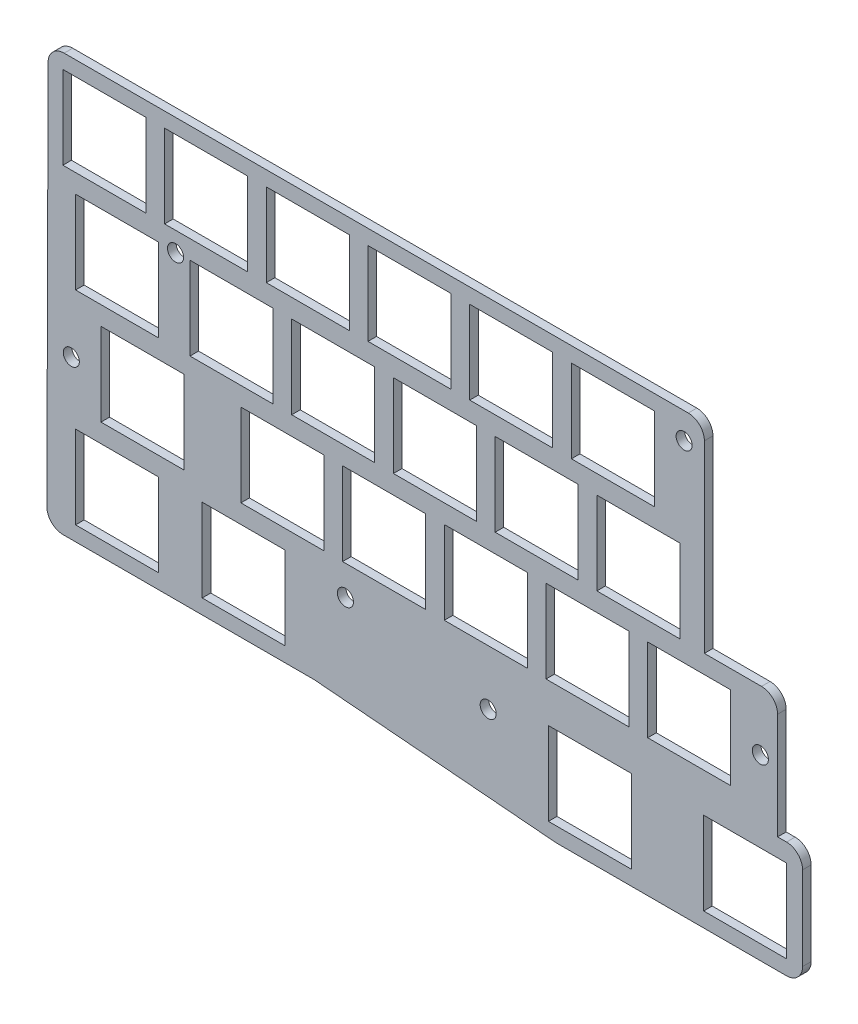
SolidWorks part; units mm, degrees
ref_plane "Front Plane" through (0, 0, 0) normal (0, 0, 1) x (1, 0, 0)
ref_plane "Top Plane" through (0, 0, 0) normal (0, 1, 0) x (1, 0, 0)
ref_plane "Right Plane" through (0, 0, 0) normal (1, 0, 0) x (0, 0, -1)
sketch "Sketch1" plane through (0, 0, 0) normal (0, 0, 1) x (1, 0, 0)
  line B0 (80.807, -9.202) -> (80.807, 37.7092)
  line B1 (77.8051, 40.7092) -> (-72.1545, 40.6131)
  arc B2 (-72.1545, 40.6131) -> (-75.1525, 37.6227) centre (-72.1526, 37.6131) ccw
  line B3 (-75.1525, 37.6227) -> (-75.3833, -34.3792)
  arc B4 (-75.3833, -34.3792) -> (-72.3833, -37.3888) centre (-72.3833, -34.3888) ccw
  line B5 (-72.3833, -37.3888) -> (-25.6137, -37.3888)
  arc B6 (-25.3626, -37.3994) -> (-25.6137, -37.3888) centre (-25.6137, -40.3888) ccw
  line B7 (-25.3626, -37.3994) -> (19.6317, -41.1783)
  arc B8 (19.6317, -41.1783) -> (19.8828, -41.1888) centre (19.8828, -38.1888) ccw
  line B9 (19.8828, -41.1888) -> (68.1448, -41.1888)
  arc B10 (68.1448, -41.1888) -> (70.9908, -39.1375) centre (68.1448, -38.1888) ccw
  line B11 (70.9908, -39.1375) -> (80.6531, -10.1507)
  arc B12 (80.6531, -10.1507) -> (80.807, -9.202) centre (77.807, -9.202) ccw
  arc B13 (80.807, 37.7092) -> (77.8051, 40.7092) centre (77.807, 37.7092) ccw
  circle B14 centre (-19.613, -21.1888) radius 1.5
  circle B15 centre (7.057, -25.9388) radius 1.5
  circle B16 centre (43.657, 35.8112) radius 1.5
  circle B17 centre (-70.818, -7.8888) radius 1.5
  circle B18 centre (57.907, -7.8888) radius 1.5
  circle B19 centre (-51.343, 18.7112) radius 1.5
  line B20 (-72.393, 22.3612) -> (-56.893, 22.3612)
  line B21 (-56.893, 22.3612) -> (-56.893, 37.8612)
  line B22 (-56.893, 37.8612) -> (-72.393, 37.8612)
  line B23 (-72.393, 37.8612) -> (-72.393, 22.3612)
  line B24 (-53.393, 22.3612) -> (-37.893, 22.3612)
  line B25 (-37.893, 22.3612) -> (-37.893, 37.8612)
  line B26 (-37.893, 37.8612) -> (-53.393, 37.8612)
  line B27 (-53.393, 37.8612) -> (-53.393, 22.3612)
  line B28 (-34.393, 22.3612) -> (-18.893, 22.3612)
  line B29 (-18.893, 22.3612) -> (-18.893, 37.8612)
  line B30 (-18.893, 37.8612) -> (-34.393, 37.8612)
  line B31 (-34.393, 37.8612) -> (-34.393, 22.3612)
  line B32 (-15.393, 22.3612) -> (0.107, 22.3612)
  line B33 (0.107, 22.3612) -> (0.107, 37.8612)
  line B34 (0.107, 37.8612) -> (-15.393, 37.8612)
  line B35 (-15.393, 37.8612) -> (-15.393, 22.3612)
  line B36 (3.607, 22.3612) -> (19.107, 22.3612)
  line B37 (19.107, 22.3612) -> (19.107, 37.8612)
  line B38 (19.107, 37.8612) -> (3.607, 37.8612)
  line B39 (3.607, 37.8612) -> (3.607, 22.3612)
  line B40 (22.607, 22.3612) -> (38.107, 22.3612)
  line B41 (38.107, 22.3612) -> (38.107, 37.8612)
  line B42 (38.107, 37.8612) -> (22.607, 37.8612)
  line B43 (22.607, 37.8612) -> (22.607, 22.3612)
  line B44 (-70.018, 3.3612) -> (-54.518, 3.3612)
  line B45 (-54.518, 3.3612) -> (-54.518, 18.8612)
  line B46 (-54.518, 18.8612) -> (-70.018, 18.8612)
  line B47 (-70.018, 18.8612) -> (-70.018, 3.3612)
  line B48 (-48.643, 3.3612) -> (-33.143, 3.3612)
  line B49 (-33.143, 3.3612) -> (-33.143, 18.8612)
  line B50 (-33.143, 18.8612) -> (-48.643, 18.8612)
  line B51 (-48.643, 18.8612) -> (-48.643, 3.3612)
  line B52 (-29.643, 3.3612) -> (-14.143, 3.3612)
  line B53 (-14.143, 3.3612) -> (-14.143, 18.8612)
  line B54 (-14.143, 18.8612) -> (-29.643, 18.8612)
  line B55 (-29.643, 18.8612) -> (-29.643, 3.3612)
  line B56 (-10.643, 3.3612) -> (4.857, 3.3612)
  line B57 (4.857, 3.3612) -> (4.857, 18.8612)
  line B58 (4.857, 18.8612) -> (-10.643, 18.8612)
  line B59 (-10.643, 18.8612) -> (-10.643, 3.3612)
  line B60 (8.357, 3.3612) -> (23.857, 3.3612)
  line B61 (23.857, 3.3612) -> (23.857, 18.8612)
  line B62 (23.857, 18.8612) -> (8.357, 18.8612)
  line B63 (8.357, 18.8612) -> (8.357, 3.3612)
  line B64 (27.357, 3.3612) -> (42.857, 3.3612)
  line B65 (42.857, 3.3612) -> (42.857, 18.8612)
  line B66 (42.857, 18.8612) -> (27.357, 18.8612)
  line B67 (27.357, 18.8612) -> (27.357, 3.3612)
  line B68 (-65.268, -15.6388) -> (-49.768, -15.6388)
  line B69 (-49.768, -15.6388) -> (-49.768, -0.1388)
  line B70 (-49.768, -0.1388) -> (-65.268, -0.1388)
  line B71 (-65.268, -0.1388) -> (-65.268, -15.6388)
  line B72 (-39.143, -15.6388) -> (-23.643, -15.6388)
  line B73 (-23.643, -15.6388) -> (-23.643, -0.1388)
  line B74 (-23.643, -0.1388) -> (-39.143, -0.1388)
  line B75 (-39.143, -0.1388) -> (-39.143, -15.6388)
  line B76 (-20.143, -15.6388) -> (-4.643, -15.6388)
  line B77 (-4.643, -15.6388) -> (-4.643, -0.1388)
  line B78 (-4.643, -0.1388) -> (-20.143, -0.1388)
  line B79 (-20.143, -0.1388) -> (-20.143, -15.6388)
  line B80 (-1.143, -15.6388) -> (14.357, -15.6388)
  line B81 (14.357, -15.6388) -> (14.357, -0.1388)
  line B82 (14.357, -0.1388) -> (-1.143, -0.1388)
  line B83 (-1.143, -0.1388) -> (-1.143, -15.6388)
  line B84 (17.857, -15.6388) -> (33.357, -15.6388)
  line B85 (33.357, -15.6388) -> (33.357, -0.1388)
  line B86 (33.357, -0.1388) -> (17.857, -0.1388)
  line B87 (17.857, -0.1388) -> (17.857, -15.6388)
  line B88 (36.857, -15.6388) -> (52.357, -15.6388)
  line B89 (52.357, -15.6388) -> (52.357, -0.1388)
  line B90 (52.357, -0.1388) -> (36.857, -0.1388)
  line B91 (36.857, -0.1388) -> (36.857, -15.6388)
  line B92 (-70.018, -34.6388) -> (-54.518, -34.6388)
  line B93 (-54.518, -34.6388) -> (-54.518, -19.1388)
  line B94 (-54.518, -19.1388) -> (-70.018, -19.1388)
  line B95 (-70.018, -19.1388) -> (-70.018, -34.6388)
  line B96 (-46.363, -34.6388) -> (-30.863, -34.6388)
  line B97 (-30.863, -34.6388) -> (-30.863, -19.1388)
  line B98 (-30.863, -19.1388) -> (-46.363, -19.1388)
  line B99 (-46.363, -19.1388) -> (-46.363, -34.6388)
  line B100 (18.307, -38.4388) -> (33.807, -38.4388)
  line B101 (33.807, -38.4388) -> (33.807, -22.9388)
  line B102 (33.807, -22.9388) -> (18.307, -22.9388)
  line B103 (18.307, -22.9388) -> (18.307, -38.4388)
  line B104 (47.307, -38.4388) -> (62.807, -38.4388)
  line B105 (62.807, -38.4388) -> (62.807, -22.9388)
  line B106 (62.807, -22.9388) -> (47.307, -22.9388)
  line B107 (47.307, -22.9388) -> (47.307, -38.4388)
sketch_block_instance "switch_plate-1"
sketch_block "switch_plate"
extrude "Boss-Extrude1" add sketch "Sketch1" along normal blind 1.6
sketch "Sketch3" plane through (0, 0, 1.6) normal (0, 0, 1) x (1, 0, 0)
  line L0 (47.4432, 42.5608) -> (47.4432, 3.3001)
  line L1 (47.4432, 3.3001) -> (61.1201, 3.3001)
  line L2 (61.1201, 3.3001) -> (61.1201, -19.5483)
  line L3 (61.1201, -19.5483) -> (65.7863, -19.5483)
  line L4 (65.7863, -19.5483) -> (65.7863, -41.1888)
  line L5 (19.8828, -41.1888) -> (68.1448, -41.1888) construction
  line L6 (65.7863, -41.1888) -> (73.3589, -43.5148)
  line L7 (73.3589, -43.5148) -> (105.294, 60.4543)
  line L8 (105.294, 60.4543) -> (47.4432, 42.5608)
extrude "Cut-Extrude2" cut sketch "Sketch3" against normal through all
fillet "Fillet2" radius 3 3 edges at (47.4432, 40.6898, 0.8) (61.1201, 3.3001, 0.8) (65.7863, -19.5483, 0.8)
fillet "Fillet3" radius 3 1 edges at (65.7863, -41.1888, 0.8)
